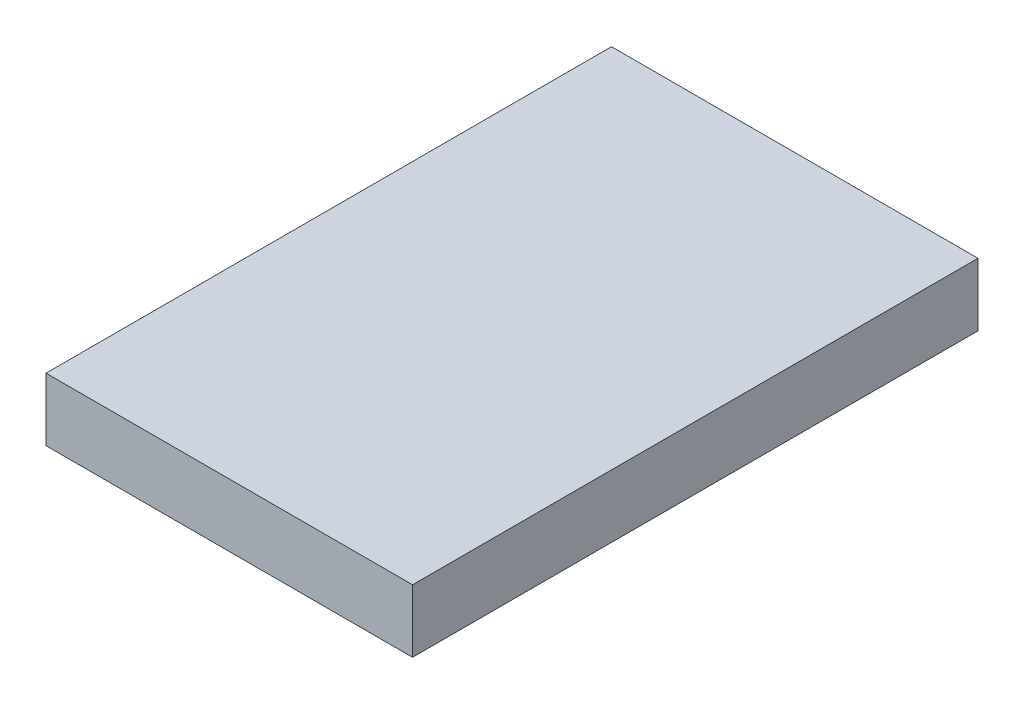
SolidWorks part; units mm, degrees
material "ABS"
ref_plane "Front Plane" through (0, 0, 0) normal (0, 0, 1) x (1, 0, 0)
ref_plane "Top Plane" through (0, 0, 0) normal (0, 1, 0) x (1, 0, 0)
ref_plane "Right Plane" through (0, 0, 0) normal (1, 0, 0) x (0, 0, -1)
sketch "Sketch1" plane through (0, 0, 0) normal (0, 1, 0) x (1, 0, 0)
  line L1 (0, 0) -> (55.5625, 0)
  line L2 (0, 0) -> (0, 85.725)
  line L3 (0, 85.725) -> (55.5625, 85.725)
  line L4 (55.5625, 0) -> (55.5625, 85.725)
  dimension "D1" = 85.725
  dimension "D2" = 55.5625
extrude "Boss-Extrude1" add sketch "Sketch1" along normal blind 9.525
